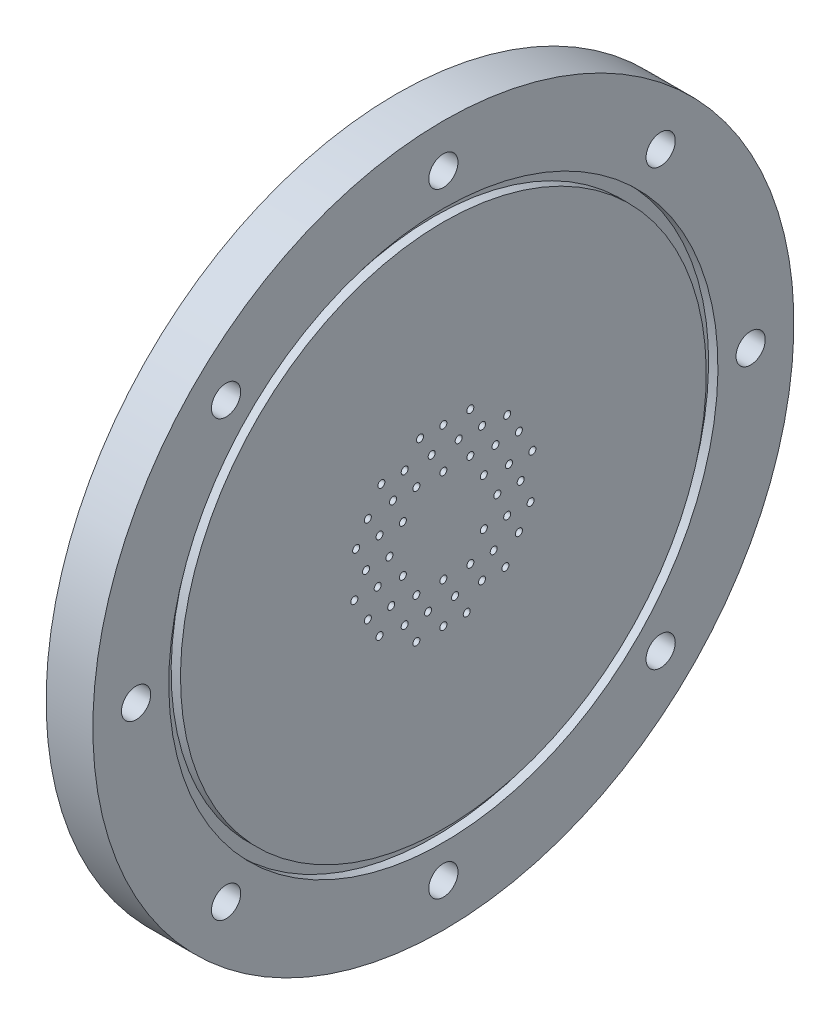
SolidWorks part; units mm, degrees
ref_plane "Front Plane" through (0, 0, 0) normal (0, 0, 1) x (1, 0, 0)
ref_plane "Top Plane" through (0, 0, 0) normal (0, 1, 0) x (1, 0, 0)
ref_plane "Right Plane" through (0, 0, 0) normal (1, 0, 0) x (0, 0, -1)
sketch "Sketch1" plane through (0, 0, 0) normal (0, 0, 1) x (1, 0, 0)
  line L0 (0, 0) -> (0, 48.26)
  line L1 (-2.54, 50.8) -> (-6.35, 50.8)
  line L2 (-6.35, 50.8) -> (-6.35, 76.2)
  line L3 (-6.35, 76.2) -> (3.81, 76.2)
  line L4 (3.81, 76.2) -> (3.81, 0)
  line L5 (3.81, 0) -> (0, 0)
  line L6 (-6.35, 50.8) -> (-6.35, 0) construction
  line L7 (-6.35, 0) -> (0, 0) construction
  arc A0 (0, 48.26) -> (-2.54, 50.8) centre (-2.54, 48.26) ccw
  dimension "D3" = 2.54
  dimension "D1" = 3.81
  dimension "D2" = 152.4
  dimension "D4" = 25.4
  dimension "D5" = 6.35
revolve "Revolve1" add sketch "Sketch1" angle 360 about L7
sketch "Sketch2" plane through (3.81, 0, 0) normal (1, 0, 0) x (0, 0, -1)
  line L0 (5.8659, 10.16) -> (3.3259, 14.5594) construction
  line L19 (21.8918, 0) -> (10.9459, 18.9588) construction
  line L20 (10.9459, 18.9588) -> (-10.9459, 18.9588) construction
  line L21 (-10.9459, 18.9588) -> (-21.8918, 0) construction
  line L22 (-21.8918, 0) -> (-10.9459, -18.9588) construction
  line L23 (-10.9459, -18.9588) -> (10.9459, -18.9588) construction
  line L24 (10.9459, -18.9588) -> (21.8918, 0) construction
  line L25 (16.8118, 0) -> (8.4059, 14.5594) construction
  line L26 (8.4059, 14.5594) -> (-8.4059, 14.5594) construction
  line L27 (-8.4059, 14.5594) -> (-16.8118, 0) construction
  line L28 (-16.8118, 0) -> (-8.4059, -14.5594) construction
  line L29 (-8.4059, -14.5594) -> (8.4059, -14.5594) construction
  line L30 (8.4059, -14.5594) -> (16.8118, 0) construction
  line L31 (11.7318, 0) -> (5.8659, 10.16) construction
  line L32 (5.8659, 10.16) -> (-5.8659, 10.16) construction
  line L33 (-5.8659, 10.16) -> (-11.7318, 0) construction
  line L34 (-11.7318, 0) -> (-5.8659, -10.16) construction
  line L35 (-5.8659, -10.16) -> (5.8659, -10.16) construction
  line L36 (5.8659, -10.16) -> (11.7318, 0) construction
  line L37 (0, 0) -> (11.7318, 0) construction
  line L38 (0, 10.16) -> (-2.54, 14.5594) construction
  line L39 (-2.54, 14.5594) -> (-5.08, 18.9588) construction
  line L40 (-5.08, 18.9588) -> (0, 18.9588) construction
  line L41 (8.4059, 14.5594) -> (5.8659, 18.9588) construction
  circle A0 centre (0, 0) radius 18.9588 construction
  circle A1 centre (0, 0) radius 14.5594 construction
  circle A2 centre (0, 0) radius 10.16 construction
  circle A3 centre (0, 10.16) radius 0.762
  circle A4 centre (0, 18.9588) radius 0.762
  circle A5 centre (5.8659, 10.16) radius 0.762
  circle A6 centre (8.4059, 14.5594) radius 0.762
  circle A7 centre (-2.54, 14.5594) radius 0.762
  circle A8 centre (5.8659, 18.9588) radius 0.762
  circle A9 centre (-5.08, 18.9588) radius 0.762
  circle A10 centre (3.3259, 14.5594) radius 0.762
  point P36 (0, 0)
  point P37 (0, 0)
  point P38 (0, 0)
  point P39 (0, 0)
  point P40 (-23.1936, 0)
  point P41 (-10.9163, 18.9077)
  dimension "D1" = 20.32
  dimension "D4" = 1.524
  dimension "D2" = 5.08
extrude "Cut-Extrude1" cut sketch "Sketch2" against normal through all
pattern_circular "CirPattern1" count 6 over 360 about axis through (0, 0, 0) along (1, 0, 0) of "Cut-Extrude1"
sketch "Sketch3" plane through (3.81, 0, 0) normal (1, 0, 0) x (0, 0, -1)
  line L0 (-66.802, 0) -> (0, 0) construction
  circle A0 centre (-66.802, 0) radius 3.175
  dimension "D1" = 6.35
  dimension "D2" = 66.802
extrude "Cut-Extrude2" cut sketch "Sketch3" against normal through all
pattern_circular "CirPattern2" count 8 over 360 about axis through (0, 0, 0) along (1, 0, 0) of "Cut-Extrude2"
sketch "Sketch4" plane through (0, 0, 0) normal (0, 0, 1) x (1, 0, 0)
  line L0 (3.81, -76.2) -> (3.81, 76.2) construction
  line L1 (3.81, 59.69) -> (1.778, 59.69)
  line L2 (3.81, 59.69) -> (3.81, 57.15)
  line L3 (3.81, 57.15) -> (1.778, 57.15)
  line L4 (1.778, 59.69) -> (1.778, 57.15)
  line L5 (-6.35, 76.2) -> (-6.35, -76.2) construction
  line L6 (-6.35, 59.69) -> (-4.318, 59.69)
  line L7 (-6.35, 59.69) -> (-6.35, 57.15)
  line L8 (-6.35, 57.15) -> (-4.318, 57.15)
  line L9 (-4.318, 59.69) -> (-4.318, 57.15)
  line L11 (0, 0) -> (-6.35, 0) construction
  line L13 (-6.35, 50.8) -> (-5.08, 50.8)
  line L14 (-6.35, 50.8) -> (-6.35, 53.34)
  line L15 (-6.35, 53.34) -> (-5.08, 53.34)
  line L16 (-5.08, 50.8) -> (-5.08, 53.34)
  dimension "D3" = 2.54
  dimension "D1" = 2.032
  dimension "D4" = 2.54
  dimension "D5" = 1.27
  dimension "D2" = 57.15
revolve "Cut-Revolve1" cut sketch "Sketch4" angle 360 about L11
chamfer "Chamfer1" distance 0.508 angle 45 48 edges at (0, -13.7974, -13.4859) (0, -13.7974, -8.4059) (0, -18.1968, -5.08) (0, -18.1968, 0) (0, -13.7974, -2.54) (0, -13.7974, 3.3259) (0, -18.1968, 5.8659) (0, -13.7974, 8.4059) (0, -13.1168, 13.8788) (0, -8.7174, 11.3388) (0, -4.318, 8.7988) (0, -9.398, 5.8659) (0, -9.398, 0) (0, -9.398, -5.8659) (0, -9.398, -10.9459) (0, -8.7174, -16.4188) (0, -4.318, -18.9588) (0, -4.318, -13.8788) (0, -4.318, -8.7988) (0, 0.762, -16.8118) (0, 5.1614, -19.3518) (0, 0.762, -11.7318) (0, 5.1614, -14.2718) (0, 10.2414, -16.4188) (0, 14.6408, -13.8788) (0, 10.2414, -11.3388) (0, 5.842, -8.7988) (0, 10.922, -5.8659) (0, 15.3214, -8.4059) (0, 19.7208, -5.8659) (0, 15.3214, -3.3259) (0, 10.922, 0) (0, 0.762, 11.7318) (0, 5.842, 8.7988) (0, 10.922, 5.8659) (0, 15.3214, 2.54) (0, 19.7208, 0) (0, 19.7208, 5.08) (0, 10.922, 10.9459) (0, 5.842, 13.8788) (0, -3.6374, 14.2718) (0, -8.7174, 16.4188) (0, -3.6374, 19.3518) (0, 0.762, 16.8118) (0, 5.842, 18.9588) (0, 10.2414, 16.4188) (0, 15.3214, 13.4859) (0, 15.3214, 8.4059)
equation "\"Injector plate Main Thickness\"=0.15"
equation "\"D1@Sketch1\"=\"Injector plate Main Thickness\""
equation "\"Comp\"=6"
equation "\"D2@Sketch1\"=\"Comp\""
equation "\"Injector Plate Edge Curve\"=0.1"
equation "\"D3@Sketch1\"=\"Injector Plate Edge Curve\""
equation "\"Injector Plate Boundry\"=1"
equation "\"D4@Sketch1\"=\"Injector Plate Boundry\""
equation "\"Injector Plate Manifold Height\"=0.25"
equation "\"D5@Sketch1\"=\"Injector Plate Manifold Height\""
equation "\"Injector Plate Holes\"=0.06"
equation "\"D4@Sketch2\"=\"Injector Plate Holes\""
equation "\"Screw Hole Diameter\"=0.25"
equation "\"D1@Sketch3\"=\"Screw Hole Diameter\""
equation "\"Injector Plate Screw Hole Distance\"=2.63"
equation "\"D2@Sketch3\"=\"Injector Plate Screw Hole Distance\""
equation "\"Injector Plate Hole Chamfer\"= 0.02"
equation "\"D1@Chamfer1\"=\"Injector Plate Hole Chamfer\""
equation "\"Locating Ring Width\"=0.1"
equation "\"D4@Sketch4\"=\"Locating Ring Width\""
equation "\"Locating Ring Depth\"=0.05"
equation "\"D5@Sketch4\"=\"Locating Ring Depth\""
equation "\"O-Ring Depth\"=0.08"
equation "\"D1@Sketch4\"=\"O-Ring Depth\""
equation "\"O-Ring Width\"=0.1"
equation "\"D3@Sketch4\"=\"O-Ring Width\""
equation "\"O-Ring Radius\"=2.25"
equation "\"D2@Sketch4\"=\"O-Ring Radius\""
